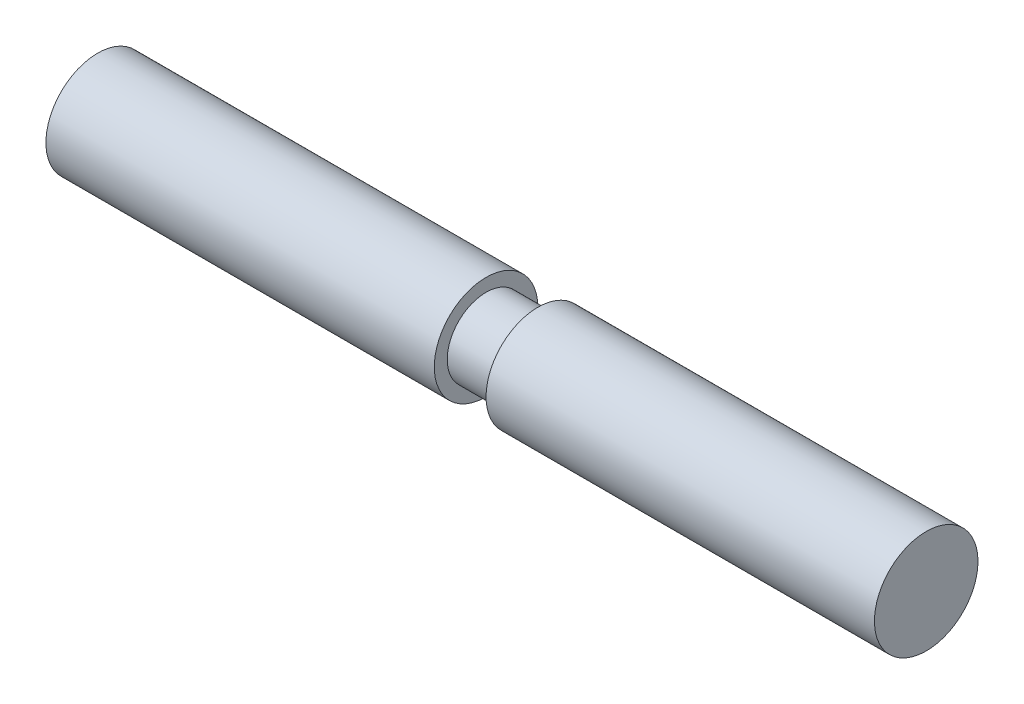
SolidWorks part; units mm, degrees
ref_plane "Front Plane" through (0, 0, 0) normal (0, 0, 1) x (1, 0, 0)
ref_plane "Top Plane" through (0, 0, 0) normal (0, 1, 0) x (1, 0, 0)
ref_plane "Right Plane" through (0, 0, 0) normal (1, 0, 0) x (0, 0, -1)
sketch "Sketch2" plane through (0, 0, 0) normal (0, 0, 1) x (1, 0, 0)
  line L0 (-24, 0) -> (24, 0) construction
  point P3 (0, 0)
ref_plane "Plane1" through (24, 0, 0) normal (1, 0, 0) x (0, 0, -1)
sketch "Sketch3" plane through (24, 0, 0) normal (1, 0, 0) x (0, 0, -1)
  circle A0 centre (0, 0) radius 6
extrude "Boss-Extrude1" add sketch "Sketch3" against normal blind 96
ref_plane "Plane2" through (-24, 0, 0) normal (1, 0, 0) x (0, 0, -1)
sketch "Sketch4" plane through (-24, 0, 0) normal (1, 0, 0) x (0, 0, -1)
  circle A0 centre (0, 0) radius 4.5
  circle A1 centre (0, 0) radius 7.6592
extrude "Cut-Extrude1" cut sketch "Sketch4" against normal mid plane 6
